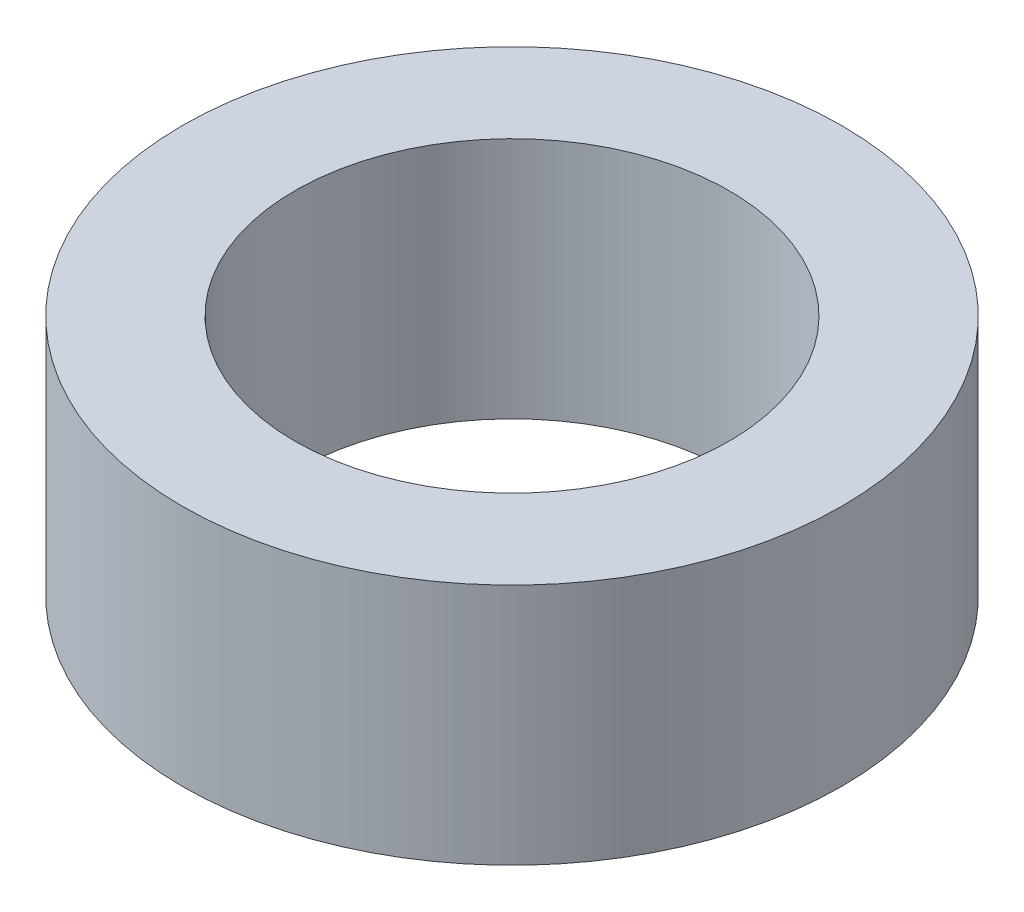
SolidWorks part; units mm, degrees
ref_plane "Front Plane" through (0, 0, 0) normal (0, 0, 1) x (1, 0, 0)
ref_plane "Top Plane" through (0, 0, 0) normal (0, 1, 0) x (1, 0, 0)
ref_plane "Right Plane" through (0, 0, 0) normal (1, 0, 0) x (0, 0, -1)
sketch "Sketch1" plane through (0, 0, 0) normal (0, 1, 0) x (1, 0, 0)
  circle A0 centre (0, 0) radius 6.075
  circle A1 centre (0, 0) radius 4
  dimension "D1" = 8
  dimension "D2" = 12.15
extrude "Boss-Extrude1" add sketch "Sketch1" along normal blind 4.4704
